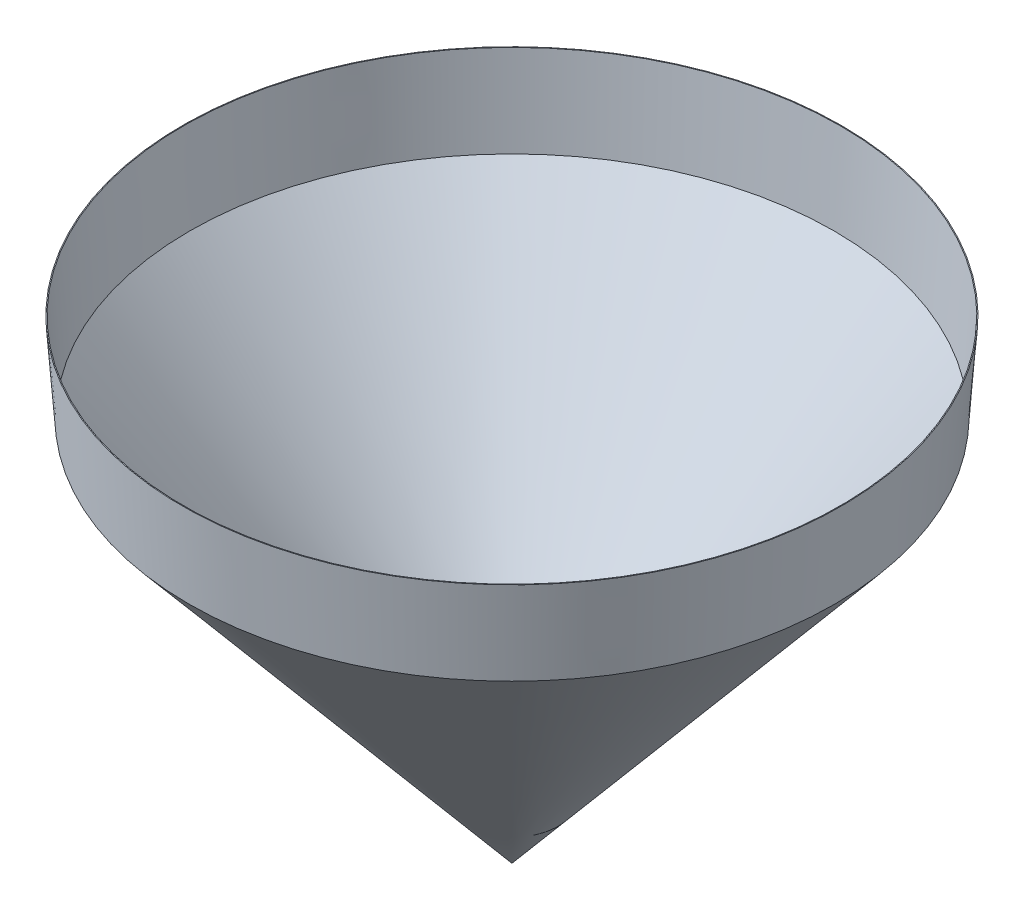
SolidWorks part; units mm, degrees
material "Nylon 6/10"
ref_plane "Front Plane" through (0, 0, 0) normal (0, 0, 1) x (1, 0, 0)
ref_plane "Top Plane" through (0, 0, 0) normal (0, 1, 0) x (1, 0, 0)
ref_plane "Right Plane" through (0, 0, 0) normal (1, 0, 0) x (0, 0, -1)
sketch "Sketch2" plane through (0, 0, 0) normal (1, 0, 0) x (0, 0, -1)
  line L0 (0, 0) -> (0, 61.1973) construction
  line L1 (-39.22, 56.4273) -> (-38.4516, 45.9493)
  line L2 (-38.4516, 45.9493) -> (0, 0)
  line L4 (-39.22, 56.4273) -> (0, 56.4273)
  line L5 (0, 56.4273) -> (0, 0)
revolve "Revolve1" add sketch "Sketch2" angle 360 about L0
shell "Shell1" thickness 0.1
